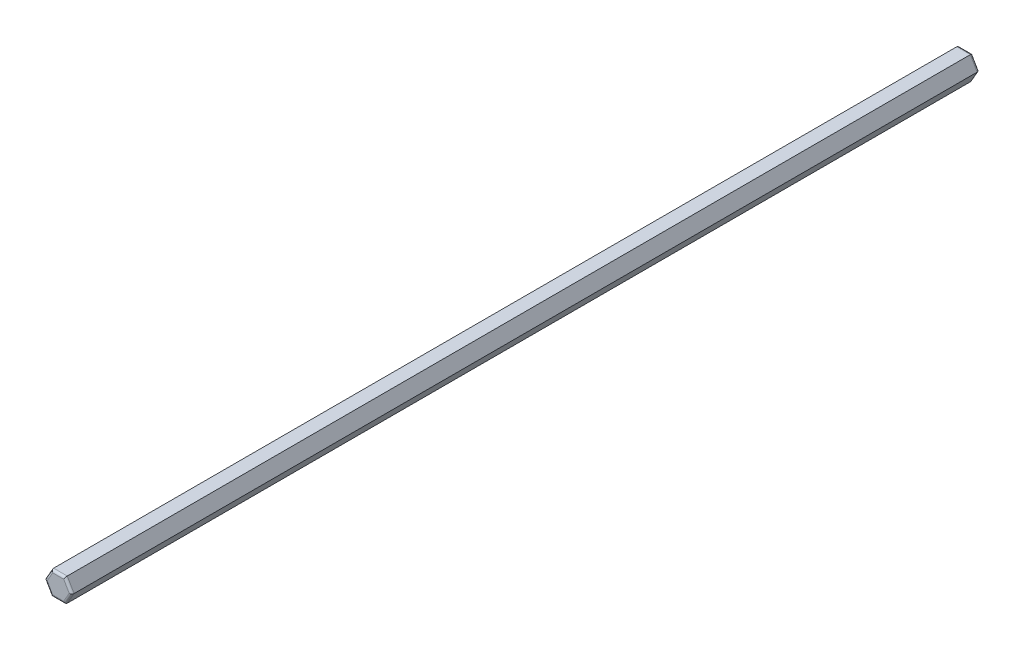
SolidWorks part; units mm, degrees
material "Liga 1060"
ref_plane "Plano frontal" through (0, 0, 0) normal (0, 0, 1) x (1, 0, 0)
ref_plane "Plano superior" through (0, 0, 0) normal (0, 1, 0) x (1, 0, 0)
ref_plane "Plano direito" through (0, 0, 0) normal (1, 0, 0) x (0, 0, -1)
ref_plane "Plano1" through (0, 0, -50) normal (0, 0, -1) x (-1, 0, 0)
sketch "Esboço1" plane through (0, 0, -50) normal (0, 0, -1) x (-1, 0, 0)
  line L0 (0.75, -1.299) -> (1.5, 0)
  line L1 (1.5, 0) -> (0.75, 1.299)
  line L2 (0.75, 1.299) -> (-0.75, 1.299)
  line L3 (-0.75, 1.299) -> (-1.5, 0)
  line L4 (-1.5, 0) -> (-0.75, -1.299)
  line L5 (-0.75, -1.299) -> (0.75, -1.299)
extrude "Ressalto-extrusão1" add sketch "Esboço1" against normal mid plane 100
fillet "Filete1" radius 0.25 12 edges at (-1.125, -0.6495, 0) (-1.125, 0.6495, 0) (0, -1.299, 0) (0, 1.299, 0) (1.125, -0.6495, 0) (1.125, 0.6495, 0) (1.125, 0.6495, -100) (1.125, -0.6495, -100) (0, 1.299, -100) (0, -1.299, -100) (-1.125, 0.6495, -100) (-1.125, -0.6495, -100)
